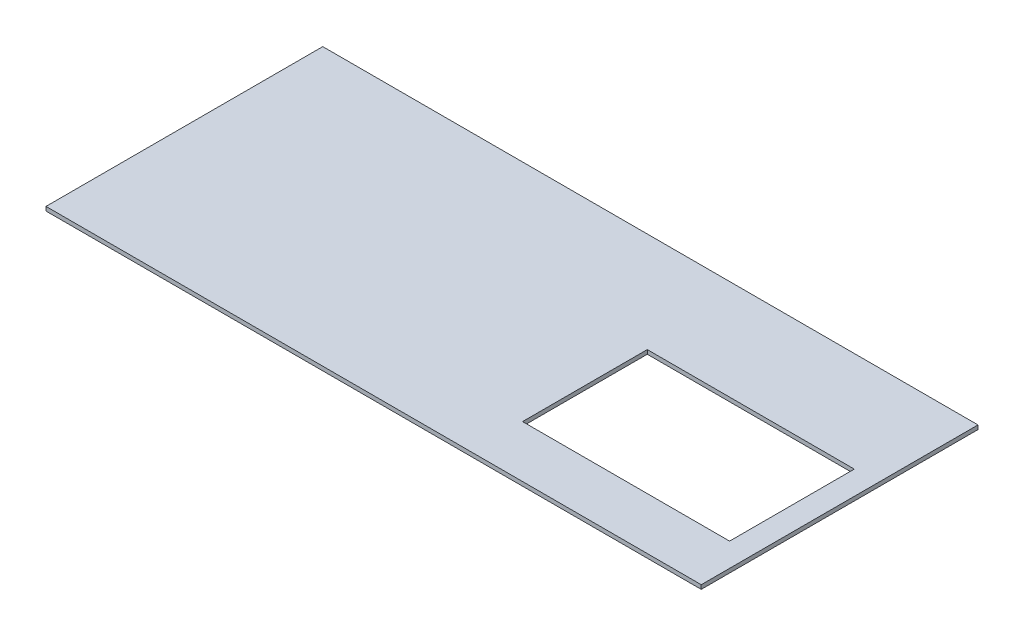
SolidWorks part; units mm, degrees
ref_plane "Front Plane" through (0, 0, 0) normal (0, 0, 1) x (1, 0, 0)
ref_plane "Top Plane" through (0, 0, 0) normal (0, 1, 0) x (1, 0, 0)
ref_plane "Right Plane" through (0, 0, 0) normal (1, 0, 0) x (0, 0, -1)
sketch "Sketch1" plane through (0, 0, 0) normal (0, 1, 0) x (1, 0, 0)
  line L0 (-255.5875, -107.95) -> (255.5875, -107.95)
  line L1 (-255.5875, -107.95) -> (-255.5875, 107.95)
  line L2 (255.5875, -107.95) -> (255.5875, 107.95)
  line L3 (-255.5875, 107.95) -> (255.5875, 107.95)
  line L4 (-255.5875, -107.95) -> (255.5875, 107.95) construction
  line L5 (255.5875, -107.95) -> (-255.5875, 107.95) construction
  point P1 (0, 0)
  dimension "D1" = 511.175
  dimension "D2" = 215.9
extrude "Boss-Extrude1" add sketch "Sketch1" along normal blind 3.175
sketch "Sketch3" plane through (0, 3.175, 0) normal (0, 1, 0) x (1, 0, 0)
  line L0 (75.6875, -67.45) -> (237.1875, -67.45)
  line L1 (75.6875, -67.45) -> (75.6875, 29.85)
  line L2 (237.1875, -67.45) -> (237.1875, 29.85)
  line L3 (75.6875, 29.85) -> (237.1875, 29.85)
  line L4 (-255.5875, -107.95) -> (255.5875, -107.95) construction
  line L6 (255.5875, -107.95) -> (255.5875, 107.95) construction
  line L7 (-255.5875, 107.95) -> (-255.5875, -107.95) construction
  line L8 (255.5875, 107.95) -> (-255.5875, 107.95) construction
  dimension "D1" = 161.5
  dimension "D2" = 97.3
  dimension "D3" = 40.5
  dimension "D4" = 18.4
  dimension "D5" = 331.275
  dimension "D6" = 78.1
extrude "Cut-Extrude1" cut sketch "Sketch3" against normal through all
